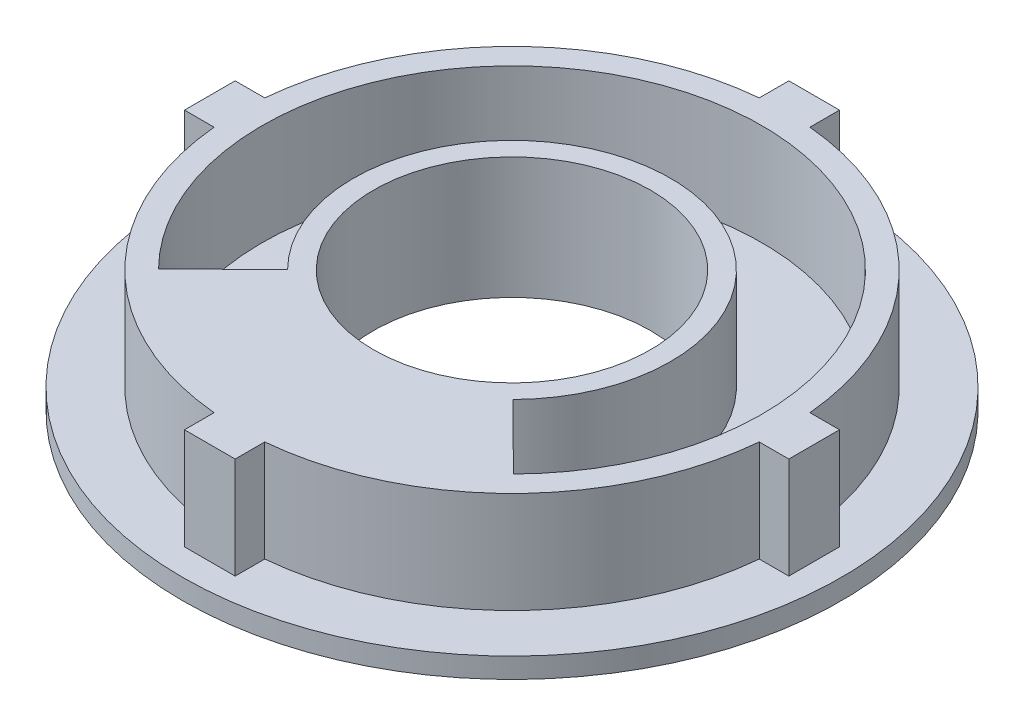
SolidWorks part; units mm, degrees
ref_plane "Front Plane" through (0, 0, 0) normal (0, 0, 1) x (1, 0, 0)
ref_plane "Top Plane" through (0, 0, 0) normal (0, 1, 0) x (1, 0, 0)
ref_plane "Right Plane" through (0, 0, 0) normal (1, 0, 0) x (0, 0, -1)
sketch "Sketch1" plane through (0, 0, 0) normal (0, 1, 0) x (1, 0, 0)
  line L0 (-17.5, -17.3601) -> (-11.1105, -11.0217)
  line L1 (0, -55) -> (0, 55) construction
  line L2 (17.5, -17.3601) -> (11.1105, -11.0217)
  line L4 (-17.5, -17.3601) -> (3.5272, -38.5567) construction
  circle A0 centre (0, 0) radius 27
  arc A1 (11.1105, -11.0217) -> (-11.1105, -11.0217) centre (0, 0) ccw
  arc A2 (17.5, -17.3601) -> (-17.5, -17.3601) centre (0, 0) ccw
  circle A3 centre (0, 0) radius 13.65
  arc A4 (16.2412, 11.7863) -> (14.3053, -14.1909) centre (0.0698, -0.0693) cw construction
  circle A5 centre (0, 0) radius 19.9533 construction
  dimension "D1" = 54
  dimension "D2" = 2.35
  dimension "D3" = 9
  dimension "D4" = 2
  dimension "D5" = 35
extrude "Boss-Extrude1" add sketch "Sketch1" along normal blind 10
sketch "Sketch2" plane through (0, 0, 0) normal (0, -1, 0) x (1, 0, 0)
  circle A0 centre (0, 0) radius 32.5
  circle A1 centre (0, 0) radius 13.65
  circle A2 centre (0, 0) radius 13.65 construction
  dimension "D1" = 65
extrude "Boss-Extrude2" add sketch "Sketch2" along normal blind 2
sketch "Sketch3" plane through (0, 0, 0) normal (0, 1, 0) x (1, 0, 0)
  line L0 (0, -55) -> (0, 55) construction
  line L1 (-2.5, 29.8) -> (2.5, 29.8)
  line L2 (-2.5, 29.8) -> (-2.5, 25.4032)
  line L3 (-2.5, 25.4032) -> (2.5, 25.4032)
  line L4 (2.5, 29.8) -> (2.5, 25.4032)
  line L5 (-2.5, 29.8) -> (2.5, 25.4032) construction
  line L6 (-2.5, 25.4032) -> (2.5, 29.8) construction
  line L7 (29.8, 2.5) -> (25.4032, 2.5)
  line L8 (29.8, 2.5) -> (29.8, -2.5)
  line L9 (29.8, -2.5) -> (25.4032, -2.5)
  line L10 (25.4032, 2.5) -> (25.4032, -2.5)
  line L11 (2.5, -29.8) -> (2.5, -25.4032)
  line L12 (2.5, -29.8) -> (-2.5, -29.8)
  line L13 (-2.5, -29.8) -> (-2.5, -25.4032)
  line L14 (2.5, -25.4032) -> (-2.5, -25.4032)
  line L15 (-29.8, -2.5) -> (-25.4032, -2.5)
  line L16 (-29.8, -2.5) -> (-29.8, 2.5)
  line L17 (-29.8, 2.5) -> (-25.4032, 2.5)
  line L18 (-25.4032, -2.5) -> (-25.4032, 2.5)
  circle A1 centre (0, 0) radius 27 construction
  point P0 (0, 27.6016)
  dimension "D2" = 29.8
  dimension "D1" = 5
  dimension "D3" = 4
extrude "Boss-Extrude3" add sketch "Sketch3" along normal blind 10
